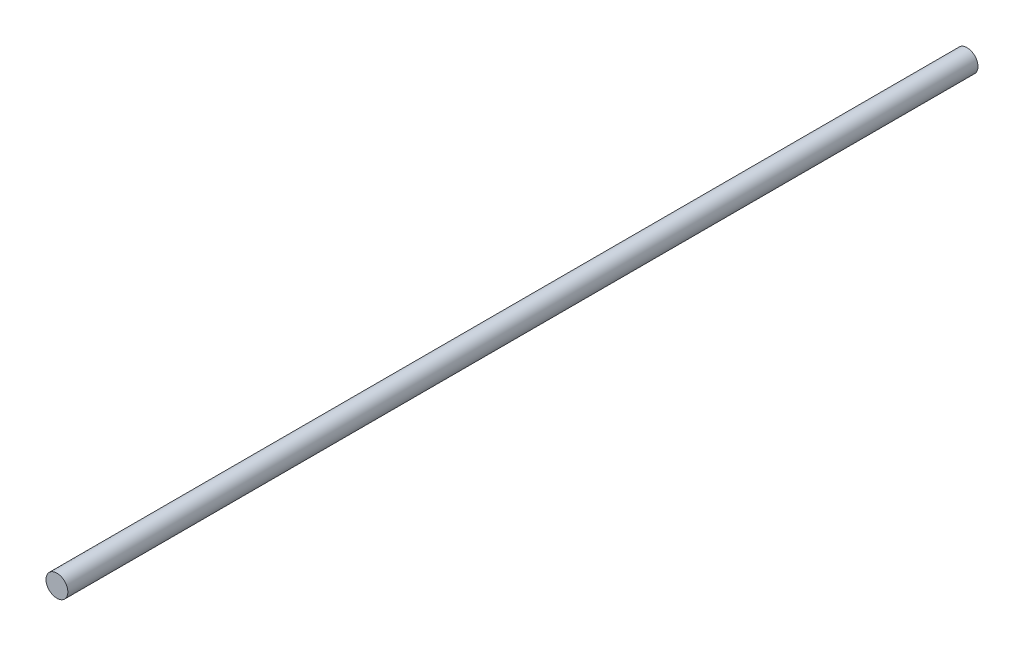
SolidWorks part; units mm, degrees
ref_plane "Front Plane" through (0, 0, 0) normal (0, 0, 1) x (1, 0, 0)
ref_plane "Top Plane" through (0, 0, 0) normal (0, 1, 0) x (1, 0, 0)
ref_plane "Right Plane" through (0, 0, 0) normal (1, 0, 0) x (0, 0, -1)
sketch "Sketch1" plane through (0, 0, 0) normal (0, 0, 1) x (1, 0, 0)
  circle A0 centre (0, 0) radius 0.9
  dimension "D1" = 1.8
extrude "Boss-Extrude1" add sketch "Sketch1" along normal blind 75
